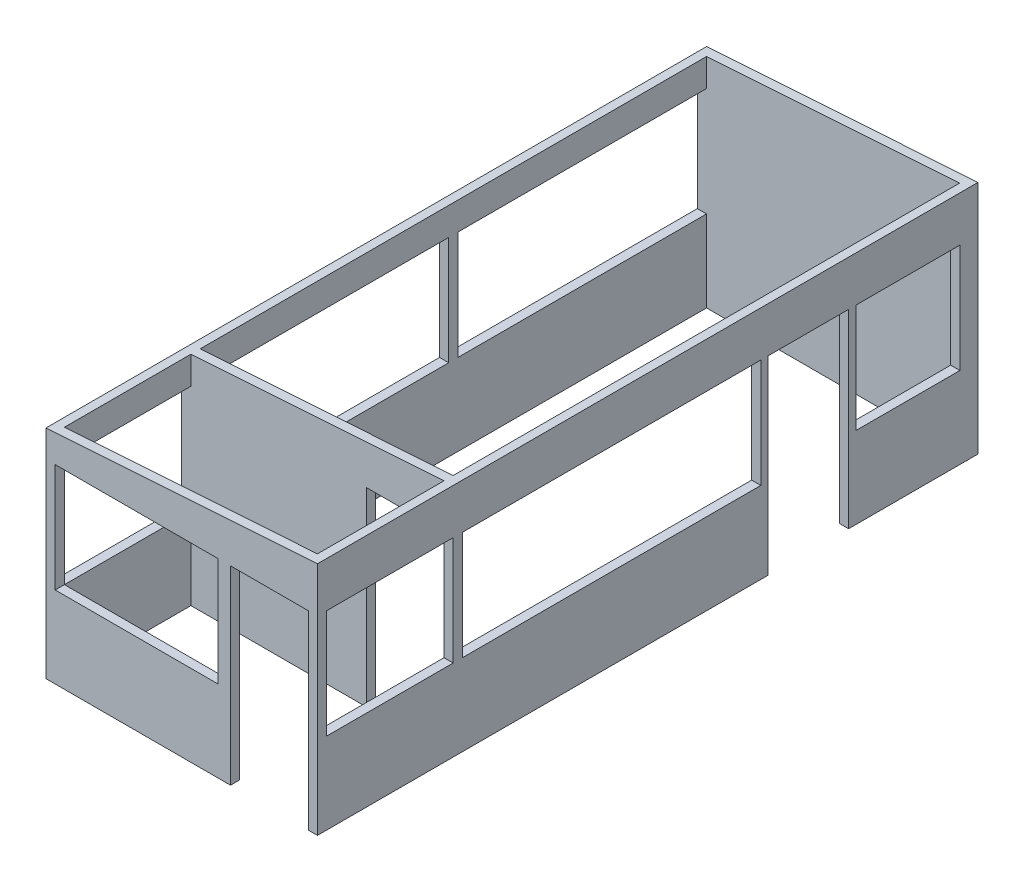
SolidWorks part; units mm, degrees
ref_plane "Alzado" through (0, 0, 0) normal (0, 0, 1) x (1, 0, 0)
ref_plane "Planta" through (0, 0, 0) normal (0, 1, 0) x (1, 0, 0)
ref_plane "Vista lateral" through (0, 0, 0) normal (1, 0, 0) x (0, 0, -1)
sketch "Croquis1" plane through (0, 0, 0) normal (0, 0, 1) x (1, 0, 0)
  line L1 (0, 0) -> (3000, 0)
  line L2 (0, 0) -> (0, 2600)
  line L3 (0, 2600) -> (3000, 2600)
  line L4 (3000, 0) -> (3000, 2600)
  dimension "D1" = 3000
  dimension "D2" = 2600
extrude "Saliente-Extruir1" add sketch "Croquis1" against normal blind 5800
sketch "Croquis3" plane through (0, 0, 0) normal (0, 0, 1) x (1, 0, 0)
  line L0 (0, 2600) -> (0, 2400)
  line L1 (0, 2600) -> (0, 0) construction
  line L2 (0, 2400) -> (3000, 2600)
  line L3 (3000, 2600) -> (0, 2600)
  dimension "D1" = 200
extrude "Cortar-Extruir1" cut sketch "Croquis3" against normal blind 5800
sketch "Croquis4" plane through (0, 0, 0) normal (-1, 0, 0) x (0, 0, 1)
  line L0 (-2900, 2400) -> (-2900, 0) construction
  line L2 (-5800, 2400) -> (0, 2400) construction
  line L4 (-5800, 0) -> (0, 0) construction
  line L6 (-5800, 2400) -> (-5800, 0) construction
  line L7 (-5698.4, 900) -> (-2950.8, 900)
  line L8 (-5698.4, 900) -> (-5698.4, 2100)
  line L9 (-5698.4, 2100) -> (-2950.8, 2100)
  line L10 (-2950.8, 900) -> (-2950.8, 2100)
  line L11 (-5698.4, 900) -> (-2950.8, 2100) construction
  line L12 (-5698.4, 2100) -> (-2950.8, 900) construction
  line L13 (0, 2400) -> (0, 0) construction
  line L14 (-101.6, 900) -> (-2849.2, 900)
  line L15 (-101.6, 900) -> (-101.6, 2100)
  line L16 (-101.6, 2100) -> (-2849.2, 2100)
  line L17 (-2849.2, 900) -> (-2849.2, 2100)
  line L18 (-101.6, 900) -> (-2849.2, 2100) construction
  line L19 (-101.6, 2100) -> (-2849.2, 900) construction
  point P6 (-4324.6, 1500)
  point P13 (-1475.4, 1500)
  dimension "D1" = 101.6
  dimension "D2" = 50.8
  dimension "D3" = 900
  dimension "D4" = 300
  dimension "D5" = 101.6
  dimension "D6" = 50.8
  dimension "D7" = 300
  dimension "D8" = 900
extrude "Cortar-Extruir2" cut sketch "Croquis4" against normal blind 101.6
sketch "Croquis6" plane through (0, 0, 0) normal (0, -1, 0) x (1, 0, 0)
  line L0 (3000, -5800) -> (3000, 0) construction
  line L1 (101.6, -101.6) -> (2898.4, -101.6)
  line L2 (101.6, -101.6) -> (101.6, -5698.4)
  line L3 (101.6, -5698.4) -> (2898.4, -5698.4)
  line L4 (2898.4, -101.6) -> (2898.4, -5698.4)
  line L5 (0, -5800) -> (3000, -5800) construction
  line L6 (0, -5800) -> (0, 0) construction
  line L7 (0, 0) -> (3000, 0) construction
  dimension "D1" = 101.6
  dimension "D2" = 101.6
  dimension "D3" = 101.6
  dimension "D4" = 101.6
extrude "Cortar-Extruir5" cut sketch "Croquis6" against normal blind 3000
sketch "Croquis13" plane through (0, 0, 0) normal (0, 0, 1) x (1, 0, 0)
  line L0 (0, 0) -> (0, 2400)
  line L1 (0, 0) -> (3000, 0)
  line L5 (0, 2400) -> (3000, 2600)
  line L6 (3000, 2600) -> (3000, 0)
extrude "Saliente-Extruir3" add sketch "Croquis13" along normal blind 1500
sketch "Croquis14" plane through (0, 0, 0) normal (0, -1, 0) x (1, 0, 0)
  line L1 (2898.4, 1398.4) -> (101.6, 1398.4)
  line L2 (2898.4, 1398.4) -> (2898.4, 0)
  line L3 (2898.4, 0) -> (101.6, 0)
  line L4 (101.6, 1398.4) -> (101.6, 0)
  line L5 (3000, -5800) -> (3000, 1500) construction
  line L6 (2898.4, -101.6) -> (101.6, -101.6) construction
  line L7 (0, -5800) -> (0, 1500) construction
  line L8 (0, 1500) -> (3000, 1500) construction
  dimension "D1" = 101.6
  dimension "D2" = 101.6
  dimension "D3" = 101.6
  dimension "D4" = 101.6
extrude "Cortar-Extruir7" cut sketch "Croquis14" against normal blind 3000
sketch "Croquis15" plane through (0, 0, 1500) normal (0, 0, 1) x (1, 0, 0)
  line L0 (0, 0) -> (3000, 0) construction
  line L1 (2039.5464, 0) -> (2898.4, 0)
  line L2 (2039.5464, 0) -> (2039.5464, 2100)
  line L3 (2039.5464, 2100) -> (2898.4, 2100)
  line L4 (2898.4, 0) -> (2898.4, 2100)
  line L5 (3000, 0) -> (3000, 2600) construction
  dimension "D1" = 101.6
  dimension "D2" = 2100
extrude "Cortar-Extruir8" cut sketch "Croquis15" against normal up to surface (1601.6 mm away) up to face at (775.4, 1375, -101.6)
sketch "Croquis16" plane through (0, 0, 0) normal (-1, 0, 0) x (0, 0, 1)
  line L0 (1398.4, 2406.7733) -> (1398.4, 0) construction
  line L1 (0, 2100) -> (1398.4, 2100)
  line L2 (0, 2100) -> (0, 900)
  line L3 (0, 900) -> (1398.4, 900)
  line L4 (1398.4, 2100) -> (1398.4, 900)
extrude "Cortar-Extruir9" cut sketch "Croquis16" against normal blind 200
sketch "Croquis17" plane through (0, 0, 1500) normal (0, 0, 1) x (1, 0, 0)
  line L0 (2039.5464, 2100) -> (2039.5464, 0) construction
  line L1 (101.6, 2100) -> (1899.5464, 2100)
  line L2 (101.6, 2100) -> (101.6, 900)
  line L3 (101.6, 900) -> (1899.5464, 900)
  line L4 (1899.5464, 2100) -> (1899.5464, 900)
  dimension "D1" = 140
extrude "Cortar-Extruir10" cut sketch "Croquis17" against normal blind 200
sketch "Croquis18" plane through (3000, 0, 0) normal (1, 0, 0) x (0, 0, -1)
  line L0 (5698.4, 900) -> (2950.8, 900) construction
  line L1 (-1398.4, 2100) -> (0, 2100)
  line L2 (-1398.4, 2100) -> (-1398.4, 900)
  line L3 (-1398.4, 900) -> (0, 900)
  line L4 (0, 2100) -> (0, 900)
  line L5 (101.6, 2100) -> (3400, 2100)
  line L6 (101.6, 2100) -> (101.6, 900)
  line L7 (101.6, 900) -> (3400, 900)
  line L8 (3400, 2100) -> (3400, 900)
  line L9 (5800, 0) -> (5800, 2600) construction
  dimension "D1" = 2400
extrude "Cortar-Extruir11" cut sketch "Croquis18" against normal blind 200
sketch "Croquis19" plane through (3000, 0, 0) normal (1, 0, 0) x (0, 0, -1)
  line L0 (3400, 900) -> (3400, 2100) construction
  line L1 (4450, 2100) -> (5600, 2100)
  line L2 (4450, 2100) -> (4450, 900)
  line L3 (4450, 900) -> (5600, 900)
  line L4 (5600, 2100) -> (5600, 900)
  dimension "D1" = 1050
  dimension "D2" = 1150
extrude "Cortar-Extruir12" cut sketch "Croquis19" against normal blind 200
sketch "Croquis20" plane through (3000, 0, 0) normal (1, 0, 0) x (0, 0, -1)
  line L0 (5800, 0) -> (-1500, 0) construction
  line L1 (3480, 2100) -> (4370, 2100)
  line L2 (3480, 2100) -> (3480, 0)
  line L3 (3480, 0) -> (4370, 0)
  line L4 (4370, 2100) -> (4370, 0)
  line L5 (3400, 900) -> (3400, 2100) construction
  line L6 (4450, 2100) -> (4450, 900) construction
  dimension "D1" = 80
  dimension "D2" = 80
extrude "Cortar-Extruir13" cut sketch "Croquis20" against normal blind 200
